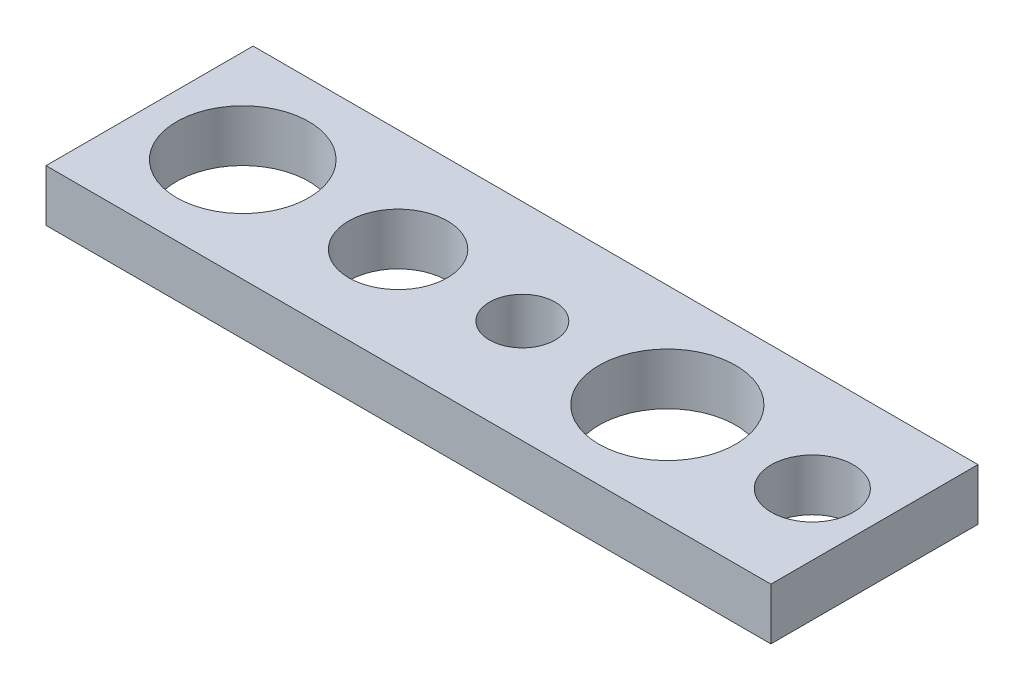
SolidWorks part; units mm, degrees
ref_plane "Plan de face" through (0, 0, 0) normal (0, 0, 1) x (1, 0, 0)
ref_plane "Plan de dessus" through (0, 0, 0) normal (0, 1, 0) x (1, 0, 0)
ref_plane "Plan de droite" through (0, 0, 0) normal (1, 0, 0) x (0, 0, -1)
sketch "Esquisse1" plane through (0, 0, 0) normal (0, 1, 0) x (1, 0, 0)
  line L1 (-15.5556, 7.7273) -> (54.4444, 7.7273)
  line L2 (-15.5556, 7.7273) -> (-15.5556, -12.2727)
  line L3 (-15.5556, -12.2727) -> (54.4444, -12.2727)
  line L4 (54.4444, 7.7273) -> (54.4444, -12.2727)
  line L5 (-15.5556, 7.7273) -> (54.4444, -12.2727) construction
  line L6 (-15.5556, -12.2727) -> (54.4444, 7.7273) construction
  point P4 (19.4444, -2.2727)
  dimension "D1" = 20
  dimension "D2" = 70
extrude "Boss.-Extru.1" add sketch "Esquisse1" along normal blind 5
sketch "Esquisse2" plane through (0, 5, 0) normal (0, 1, 0) x (1, 0, 0)
  line L0 (-15.5556, 7.7273) -> (-15.5556, -12.2727) construction
  circle A0 centre (-6.5556, -2.2727) radius 6.375
  circle A1 centre (8.4444, -2.2727) radius 4.7625
  circle A2 centre (20.4444, -2.2727) radius 3.175
  circle A3 centre (34.4444, -2.2727) radius 6.6
  circle A4 centre (48.4444, -2.2727) radius 3.9687
  point P4 (0, 0)
  point P5 (-15.5556, -2.2727)
  point P14 (0, 0)
  dimension "D1" = 12.75
  dimension "D3" = 9.525
  dimension "D5" = 6.35
  dimension "D6" = 12
  dimension "D7" = 13.2
  dimension "D9" = 7.9375
  dimension "D2" = 9
  dimension "D4" = 15
  dimension "D8" = 14
  dimension "D10" = 14
extrude "Enlèv. mat.-Extru.1" cut sketch "Esquisse2" against normal through all
